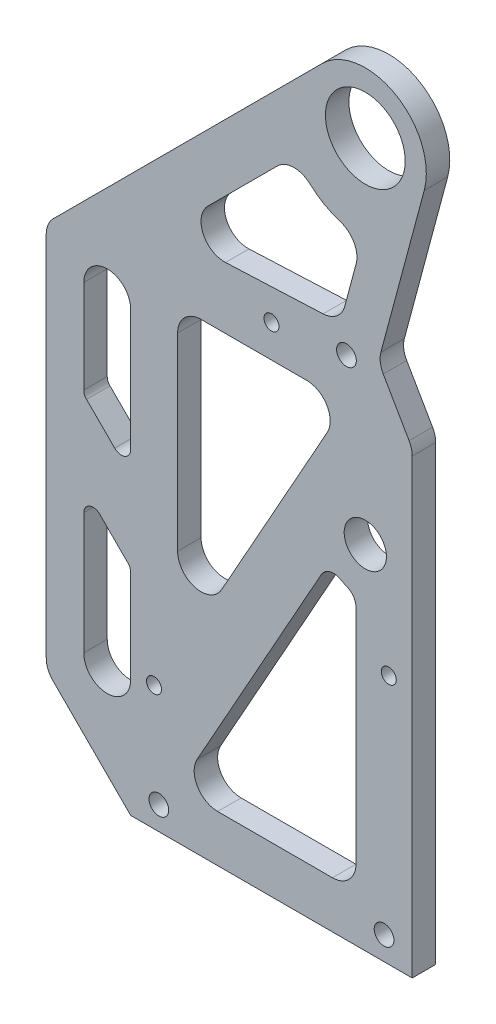
SolidWorks part; units mm, degrees
material "6061 Alloy"
ref_plane "Front Plane" through (0, 0, 0) normal (0, 0, 1) x (1, 0, 0)
ref_plane "Top Plane" through (0, 0, 0) normal (0, 1, 0) x (1, 0, 0)
ref_plane "Right Plane" through (0, 0, 0) normal (1, 0, 0) x (0, 0, -1)
sketch "Sketch1" plane through (0, 0, 0) normal (0, 0, 1) x (1, 0, 0)
  line L0 (0, 103.759) -> (0, -103.759) construction
  line L1 (-30, 76) -> (50, 76)
  line L2 (-30, 76) -> (-30, 256)
  line L3 (-30, 256) -> (50, 256)
  line L4 (50, 76) -> (50, 256)
  circle A0 centre (20, 226) radius 8.5
  dimension "D1" = 150
  dimension "D5" = 17
  dimension "D2" = 20
  dimension "D3" = 180
  dimension "D4" = 80
extrude "Boss-Extrude1" add sketch "Sketch1" along normal blind 5
sketch "Sketch2" plane through (0, 0, 5) normal (0, 0, 1) x (1, 0, 0)
  line L0 (20, 226) -> (20, 151) construction
  line L1 (20, 226) -> (-17.1819, 226) construction
  circle A0 centre (20, 151) radius 4.5
  dimension "D3" = 9
  dimension "D1" = 75
  dimension "D2" = 90
extrude "Cut-Extrude1" cut sketch "Sketch2" against normal blind 30
sketch "Sketch3" plane through (0, 0, 5) normal (0, 0, 1) x (1, 0, 0)
  circle A0 centre (0, 182) radius 1.6
  circle A1 centre (25, 129.3013) radius 1.6
  circle A2 centre (-25.0329, 102.5335) radius 1.6
  circle A3 centre (-15, 81) radius 2.5
  circle A4 centre (15, 81) radius 2.5
  circle A5 centre (24, 91) radius 2.5
  circle A6 centre (-24, 91) radius 2.5
  dimension "D1" = 5
  dimension "D2" = 3.2
extrude "Cut-Extrude2" cut sketch "Sketch3" against normal blind 5
sketch "Sketch4" plane through (0, 0, 5) normal (0, 0, 1) x (1, 0, 0)
  line L0 (10.8076, 235.1924) -> (-46.0411, 178.3437)
  line L1 (-46.0411, 178.3437) -> (-46.0411, 109.8941)
  line L2 (-46.0411, 109.8941) -> (-30, 76)
  line L3 (32.557, 222.6354) -> (22.7869, 186.1729)
  line L4 (22.7869, 186.1729) -> (30, 173.6795)
  line L5 (30, 173.6795) -> (30, 76)
  line L6 (-30, 76) -> (50, 76) construction
  line L7 (30, 76) -> (50, 76)
  line L8 (50, 76) -> (50, 256)
  line L9 (50, 256) -> (-30, 256)
  line L10 (-30, 256) -> (-68.6435, 166)
  line L11 (-68.6435, 166) -> (-57.2516, 84.4416)
  line L12 (-57.2516, 84.4416) -> (-30, 76)
  circle A0 centre (20, 226) radius 13
  circle A1 centre (20, 151) radius 4.5 construction
  line M14 (-30, 256) -> (-30, 76)
  line M15 (-30, 76) -> (50, 76)
  line M16 (50, 76) -> (50, 256)
  line M17 (50, 256) -> (-30, 256)
  dimension "D1" = 26
  dimension "D4" = 20
  dimension "D5" = 60
  dimension "D2" = 75
  dimension "D3" = 45
  dimension "D6" = 60
extrude "Cut-Extrude3" cut sketch "Sketch4" against normal blind 10 contours A0 L3 L4 L5 L0 M15 M16 M17 M14
sketch "Sketch5" plane through (0, 0, 5) normal (0, 0, 1) x (1, 0, 0)
  line L0 (-30, 194.3848) -> (-46.5355, 177.8492)
  line L1 (-48, 174.3137) -> (-48, 96.0711)
  line L2 (-46.5355, 92.5355) -> (-30, 76)
  line L4 (10.8076, 235.1924) -> (-30, 194.3848) construction
  line L6 (-30, 194.3848) -> (-30, 76) construction
  line L15 (-30, 76) -> (30, 76) construction
  line L16 (-35, 169.3848) -> (-35, 101) construction
  line L17 (-30, 169.3848) -> (-30, 101)
  line L18 (-40, 169.3848) -> (-40, 101)
  line L19 (-30, 138.6777) -> (-30, 121.7071)
  line L20 (-30, 138.6777) -> (-40, 148.6777)
  line L21 (-30, 121.7071) -> (-40, 131.7071)
  line L22 (-40, 148.6777) -> (-40, 131.7071)
  line L23 (-40, 148.6777) -> (-30, 121.7071)
  arc A0 (-30, 169.3848) -> (-40, 169.3848) centre (-35, 169.3848) ccw
  arc A1 (-40, 101) -> (-30, 101) centre (-35, 101) ccw
  arc A2 (-48, 96.0711) -> (-46.5355, 92.5355) centre (-43, 96.0711) ccw
  arc A3 (-46.5355, 177.8492) -> (-48, 174.3137) centre (-43, 174.3137) ccw
  point P14 (-35, 135.1924)
  point P26 (-48, 94)
  point P29 (-48, 176.3848)
  line M19 (-30, 194.3848) -> (-30, 76)
  dimension "D6" = 5
  dimension "D9" = 5
  dimension "D1" = 18
  dimension "D2" = 45
  dimension "D3" = 7
  dimension "D4" = 7
  dimension "D5" = 8
  dimension "D7" = 12
  dimension "D8" = 135
extrude "Boss-Extrude2" add sketch "Sketch5" against normal blind 5 contours L1 L2 L0 A1 L18 A0 L17 M19 | L16 L23 L18 L21 | L20 L16 L23 L17 | L16 L20 L23 | L23 L16 L21
fillet "Fillet1" radius 2 4 edges at (-40, 131.7071, 2.5) (-40, 148.6777, 2.5) (-30, 121.7071, 2.5) (-30, 138.6777, 2.5)
fillet "Fillet2" radius 5 2 edges at (30, 173.6795, 2.5) (22.7869, 186.1729, 2.5)
sketch "Sketch6" plane through (0, 0, 5) normal (0, 0, 1) x (1, 0, 0)
  line L0 (32.557, 222.6354) -> (23.323, 188.1734) construction
  line L1 (23.8225, 184.3793) -> (29.3301, 174.8397) construction
  circle A0 centre (15.9821, 183.9592) radius 2.1
  dimension "D1" = 4.2
  dimension "D2" = 6
  dimension "D3" = 7
extrude "Cut-Extrude4" cut sketch "Sketch6" against normal blind 5
sketch "Sketch7" plane through (0, 0, 5) normal (0, 0, 1) x (1, 0, 0)
  line L0 (30, 172.3397) -> (30, 76) construction
  line L1 (-30, 76) -> (30, 76)
  line L2 (-30, 76) -> (-30, 95.778)
  line L3 (-30, 95.778) -> (30, 95.778)
  line L4 (30, 76) -> (30, 95.778)
extrude "Boss-Extrude3" add sketch "Sketch7" against normal blind 5
sketch "Sketch8" plane through (0, 0, 5) normal (0, 0, 1) x (1, 0, 0)
  line L0 (-30, 169.3848) -> (-30, 143.5061) construction
  line L1 (-30, 76) -> (30, 76) construction
  circle A0 centre (-24, 81) radius 2.1
  circle A1 centre (24, 81) radius 2.1
  dimension "D1" = 4.2
  dimension "D2" = 6
  dimension "D3" = 54
  dimension "D4" = 5
extrude "Cut-Extrude6" cut sketch "Sketch8" against normal blind 5
sketch "Sketch9" plane through (0, 0, 5) normal (0, 0, 1) x (1, 0, 0)
  line L0 (18.046, 201.8387) -> (15.6185, 192.779)
  line L1 (1.2774, 211.52) -> (-13.5494, 196.6932)
  line L2 (11.0087, 189.078) -> (-9.7941, 188.1625)
  line L3 (-40, 126.8787) -> (-40, 101) construction
  arc A0 (8.1878, 211.6737) -> (14.7239, 207.9001) centre (20, 224.5858) ccw
  arc A1 (8.1878, 211.6737) -> (1.2774, 211.52) centre (4.8129, 207.9845) ccw
  arc A2 (14.7239, 207.9001) -> (18.046, 201.8387) centre (13.2164, 203.1328) cw
  arc A3 (-13.5494, 196.6932) -> (-9.7941, 188.1625) centre (-10.0139, 193.1577) ccw
  arc A4 (15.6185, 192.779) -> (11.0087, 189.078) centre (10.7889, 194.0731) cw
  dimension "D1" = 17.5
  dimension "D2" = 5
  dimension "D3" = 26.4506
  dimension "D4" = 29.9861
  dimension "D5" = 30.2059
  dimension "D6" = 41.2774
  dimension "D7" = 48.1878
  dimension "D8" = 50.7889
  dimension "D9" = 53.2164
  dimension "D10" = 18.7778
extrude "Cut-Extrude7" cut sketch "Sketch9" against normal blind 5
sketch "Sketch10" plane through (0, 0, 5) normal (0, 0, 1) x (1, 0, 0)
  line L0 (-20, 175.0528) -> (-20, 110.5916)
  line L1 (-20, 110.5916) -> (16.0369, 175.0528)
  line L2 (16.0369, 175.0528) -> (-20, 175.0528)
  line L3 (12.3296, 143.8296) -> (-20, 86)
  line L4 (-20, 86) -> (18, 86)
  line L5 (18, 86) -> (18, 140.6922)
  line L7 (-30, 76) -> (30, 76) construction
  line L8 (-30, 169.3848) -> (-30, 143.5061) construction
  line L9 (30, 172.3397) -> (30, 76) construction
  arc A0 (12.3296, 143.8296) -> (18, 140.6922) centre (20, 151) ccw
  circle A1 centre (20, 151) radius 4.5 construction
  circle A2 centre (20, 151) radius 4.5 construction
  dimension "D5" = 6
  dimension "D1" = 10
  dimension "D2" = 12
  dimension "D3" = 10
  dimension "D4" = 12
extrude "Cut-Extrude8" cut sketch "Sketch10" against normal blind 10
fillet "Fillet3" radius 5 5 edges at (18, 86, 2.5) (-20, 86, 2.5) (-20, 110.5916, 2.5) (16.0369, 175.0528, 2.5) (-20, 175.0528, 2.5)
fillet "Fillet4" radius 3 2 edges at (18, 140.6922, 2.5) (12.3296, 143.8296, 2.5)
